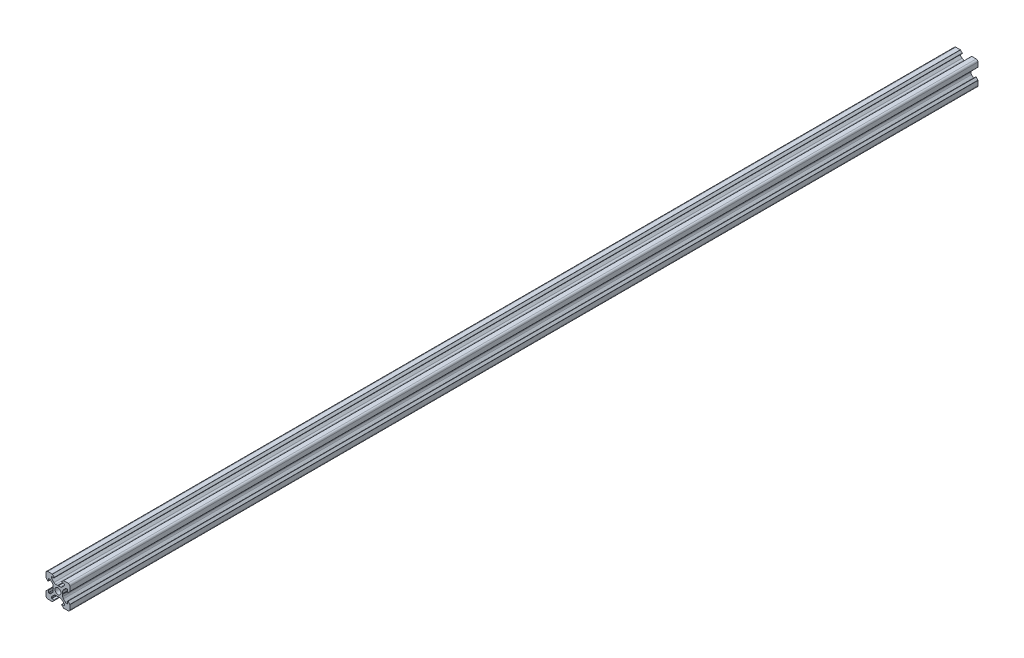
SolidWorks part; units mm, degrees
ref_plane "Спереди" through (0, 0, 0) normal (0, 0, 1) x (1, 0, 0)
ref_plane "Сверху" through (0, 0, 0) normal (0, 1, 0) x (1, 0, 0)
ref_plane "Справа" through (0, 0, 0) normal (1, 0, 0) x (0, 0, -1)
sketch "Model" plane through (0, 0, 0) normal (0, 0, 1) x (1, 0, 0)
  line L0 (18.9421, 33.3622) -> (18.9421, 34.9233)
  line L1 (18.3564, 36.3375) -> (16.6623, 38.0316)
  line L2 (15.9551, 38.3245) -> (15.1421, 38.3245)
  line L3 (14.9421, 38.1245) -> (14.9421, 36.3545)
  line L4 (13.0154, 37.6777) -> (14.5154, 36.1777)
  line L5 (12.9421, 37.8545) -> (12.9421, 41.5245)
  line L6 (18.2889, 42.9513) -> (19.7889, 41.4513)
  line L7 (22.7606, 36.9697) -> (22.9421, 36.8245)
  line L8 (23.1237, 36.9697) -> (22.9421, 36.8245)
  line L9 (23.2798, 37.0245) -> (24.8409, 37.0245)
  line L10 (26.2551, 37.6103) -> (27.9493, 39.3044)
  line L11 (28.2421, 40.0115) -> (28.2421, 40.8245)
  line L12 (28.0421, 41.0245) -> (26.2721, 41.0245)
  line L13 (27.5954, 42.9513) -> (26.0954, 41.4513)
  line L14 (27.7721, 43.0245) -> (31.4421, 43.0245)
  line L15 (32.9421, 37.8545) -> (32.9421, 41.5245)
  line L16 (32.8689, 37.6777) -> (31.3689, 36.1777)
  line L17 (30.9421, 38.1245) -> (30.9421, 36.3545)
  line L18 (29.9292, 38.3245) -> (30.7421, 38.3245)
  line L19 (27.5279, 36.3375) -> (29.222, 38.0316)
  line L20 (26.9421, 33.3622) -> (26.9421, 34.9233)
  line L21 (26.8874, 33.206) -> (26.7421, 33.0245)
  line L22 (26.8874, 32.843) -> (26.7421, 33.0245)
  line L23 (26.9421, 32.6868) -> (26.9421, 31.1257)
  line L24 (27.5279, 29.7115) -> (29.222, 28.0174)
  line L25 (29.9292, 27.7245) -> (30.7421, 27.7245)
  line L26 (30.9421, 27.9245) -> (30.9421, 29.6945)
  line L27 (32.8689, 28.3713) -> (31.3689, 29.8713)
  line L28 (32.9421, 28.1945) -> (32.9421, 24.5245)
  line L29 (27.7721, 23.0245) -> (31.4421, 23.0245)
  line L30 (27.5954, 23.0977) -> (26.0954, 24.5977)
  line L31 (28.0421, 25.0245) -> (26.2721, 25.0245)
  line L32 (28.2421, 26.0375) -> (28.2421, 25.2245)
  line L33 (26.2551, 28.4387) -> (27.9493, 26.7446)
  line L34 (23.2798, 29.0245) -> (24.8409, 29.0245)
  line L35 (23.1237, 29.0793) -> (22.9421, 29.2245)
  line L36 (22.7606, 29.0793) -> (22.9421, 29.2245)
  line L37 (19.6292, 28.4387) -> (17.935, 26.7446)
  line L38 (17.6421, 26.0375) -> (17.6421, 25.2245)
  line L39 (17.8421, 25.0245) -> (19.6121, 25.0245)
  line L40 (18.2889, 23.0977) -> (19.7889, 24.5977)
  line L41 (18.1121, 23.0245) -> (14.4421, 23.0245)
  line L42 (12.9421, 28.1945) -> (12.9421, 24.5245)
  line L43 (13.0154, 28.3713) -> (14.5154, 29.8713)
  line L44 (14.9421, 27.9245) -> (14.9421, 29.6945)
  line L45 (15.9551, 27.7245) -> (15.1421, 27.7245)
  line L46 (18.3564, 29.7115) -> (16.6623, 28.0174)
  line L47 (18.9421, 32.6868) -> (18.9421, 31.1257)
  line L48 (18.9969, 32.843) -> (19.1421, 33.0245)
  line L49 (18.9969, 33.206) -> (19.1421, 33.0245)
  line L50 (22.6045, 29.0245) -> (21.0434, 29.0245)
  line L51 (22.6045, 37.0245) -> (21.0434, 37.0245)
  line L52 (19.6292, 37.6103) -> (17.935, 39.3044)
  line L53 (17.6421, 40.0115) -> (17.6421, 40.8245)
  line L54 (17.8421, 41.0245) -> (19.6121, 41.0245)
  line L55 (18.1121, 43.0245) -> (14.4421, 43.0245)
  arc A0 (18.9421, 33.3622) -> (18.9969, 33.206) centre (19.1921, 33.3622) ccw
  arc A1 (18.9421, 34.9233) -> (18.3564, 36.3375) centre (16.9421, 34.9233) ccw
  arc A2 (16.6623, 38.0316) -> (15.9551, 38.3245) centre (15.9551, 37.3245) ccw
  arc A3 (15.1421, 38.3245) -> (14.9421, 38.1245) centre (15.1421, 38.1245) ccw
  arc A4 (14.5154, 36.1777) -> (14.9421, 36.3545) centre (14.6921, 36.3545) ccw
  arc A5 (12.9421, 37.8545) -> (13.0154, 37.6777) centre (13.1921, 37.8545) ccw
  arc A6 (14.4421, 43.0245) -> (12.9421, 41.5245) centre (14.4421, 41.5245) ccw
  arc A7 (18.2889, 42.9513) -> (18.1121, 43.0245) centre (18.1121, 42.7745) ccw
  arc A8 (19.6121, 41.0245) -> (19.7889, 41.4513) centre (19.6121, 41.2745) ccw
  arc A9 (17.8421, 41.0245) -> (17.6421, 40.8245) centre (17.8421, 40.8245) ccw
  arc A10 (17.6421, 40.0115) -> (17.935, 39.3044) centre (18.6421, 40.0115) ccw
  arc A11 (19.6292, 37.6103) -> (21.0434, 37.0245) centre (21.0434, 39.0245) ccw
  arc A12 (22.7606, 36.9697) -> (22.6045, 37.0245) centre (22.6045, 36.7745) ccw
  arc A13 (23.2798, 37.0245) -> (23.1237, 36.9697) centre (23.2798, 36.7745) ccw
  arc A14 (24.8409, 37.0245) -> (26.2551, 37.6103) centre (24.8409, 39.0245) ccw
  arc A15 (27.9493, 39.3044) -> (28.2421, 40.0115) centre (27.2421, 40.0115) ccw
  arc A16 (28.2421, 40.8245) -> (28.0421, 41.0245) centre (28.0421, 40.8245) ccw
  arc A17 (26.0954, 41.4513) -> (26.2721, 41.0245) centre (26.2721, 41.2745) ccw
  arc A18 (27.7721, 43.0245) -> (27.5954, 42.9513) centre (27.7721, 42.7745) ccw
  arc A19 (32.9421, 41.5245) -> (31.4421, 43.0245) centre (31.4421, 41.5245) ccw
  arc A20 (32.8689, 37.6777) -> (32.9421, 37.8545) centre (32.6921, 37.8545) ccw
  arc A21 (30.9421, 36.3545) -> (31.3689, 36.1777) centre (31.1921, 36.3545) ccw
  arc A22 (30.9421, 38.1245) -> (30.7421, 38.3245) centre (30.7421, 38.1245) ccw
  arc A23 (29.9292, 38.3245) -> (29.222, 38.0316) centre (29.9292, 37.3245) ccw
  arc A24 (27.5279, 36.3375) -> (26.9421, 34.9233) centre (28.9421, 34.9233) ccw
  arc A25 (26.8874, 33.206) -> (26.9421, 33.3622) centre (26.6921, 33.3622) ccw
  arc A26 (26.9421, 32.6868) -> (26.8874, 32.843) centre (26.6921, 32.6868) ccw
  arc A27 (26.9421, 31.1257) -> (27.5279, 29.7115) centre (28.9421, 31.1257) ccw
  arc A28 (29.222, 28.0174) -> (29.9292, 27.7245) centre (29.9292, 28.7245) ccw
  arc A29 (30.7421, 27.7245) -> (30.9421, 27.9245) centre (30.7421, 27.9245) ccw
  arc A30 (31.3689, 29.8713) -> (30.9421, 29.6945) centre (31.1921, 29.6945) ccw
  arc A31 (32.9421, 28.1945) -> (32.8689, 28.3713) centre (32.6921, 28.1945) ccw
  arc A32 (31.4421, 23.0245) -> (32.9421, 24.5245) centre (31.4421, 24.5245) ccw
  arc A33 (27.5954, 23.0977) -> (27.7721, 23.0245) centre (27.7721, 23.2745) ccw
  arc A34 (26.2721, 25.0245) -> (26.0954, 24.5977) centre (26.2721, 24.7745) ccw
  arc A35 (28.0421, 25.0245) -> (28.2421, 25.2245) centre (28.0421, 25.2245) ccw
  arc A36 (28.2421, 26.0375) -> (27.9493, 26.7446) centre (27.2421, 26.0375) ccw
  arc A37 (26.2551, 28.4387) -> (24.8409, 29.0245) centre (24.8409, 27.0245) ccw
  arc A38 (23.1237, 29.0793) -> (23.2798, 29.0245) centre (23.2798, 29.2745) ccw
  arc A39 (22.6045, 29.0245) -> (22.7606, 29.0793) centre (22.6045, 29.2745) ccw
  arc A40 (21.0434, 29.0245) -> (19.6292, 28.4387) centre (21.0434, 27.0245) ccw
  arc A41 (17.935, 26.7446) -> (17.6421, 26.0375) centre (18.6421, 26.0375) ccw
  arc A42 (17.6421, 25.2245) -> (17.8421, 25.0245) centre (17.8421, 25.2245) ccw
  arc A43 (19.7889, 24.5977) -> (19.6121, 25.0245) centre (19.6121, 24.7745) ccw
  arc A44 (18.1121, 23.0245) -> (18.2889, 23.0977) centre (18.1121, 23.2745) ccw
  arc A45 (12.9421, 24.5245) -> (14.4421, 23.0245) centre (14.4421, 24.5245) ccw
  arc A46 (13.0154, 28.3713) -> (12.9421, 28.1945) centre (13.1921, 28.1945) ccw
  arc A47 (14.9421, 29.6945) -> (14.5154, 29.8713) centre (14.6921, 29.6945) ccw
  arc A48 (14.9421, 27.9245) -> (15.1421, 27.7245) centre (15.1421, 27.9245) ccw
  arc A49 (15.9551, 27.7245) -> (16.6623, 28.0174) centre (15.9551, 28.7245) ccw
  arc A50 (18.3564, 29.7115) -> (18.9421, 31.1257) centre (16.9421, 31.1257) ccw
  arc A51 (18.9969, 32.843) -> (18.9421, 32.6868) centre (19.1921, 32.6868) ccw
  circle A52 centre (22.9421, 33.0245) radius 2.5
extrude "Бобышка-Вытянуть1" add sketch "Model" along normal blind 760
